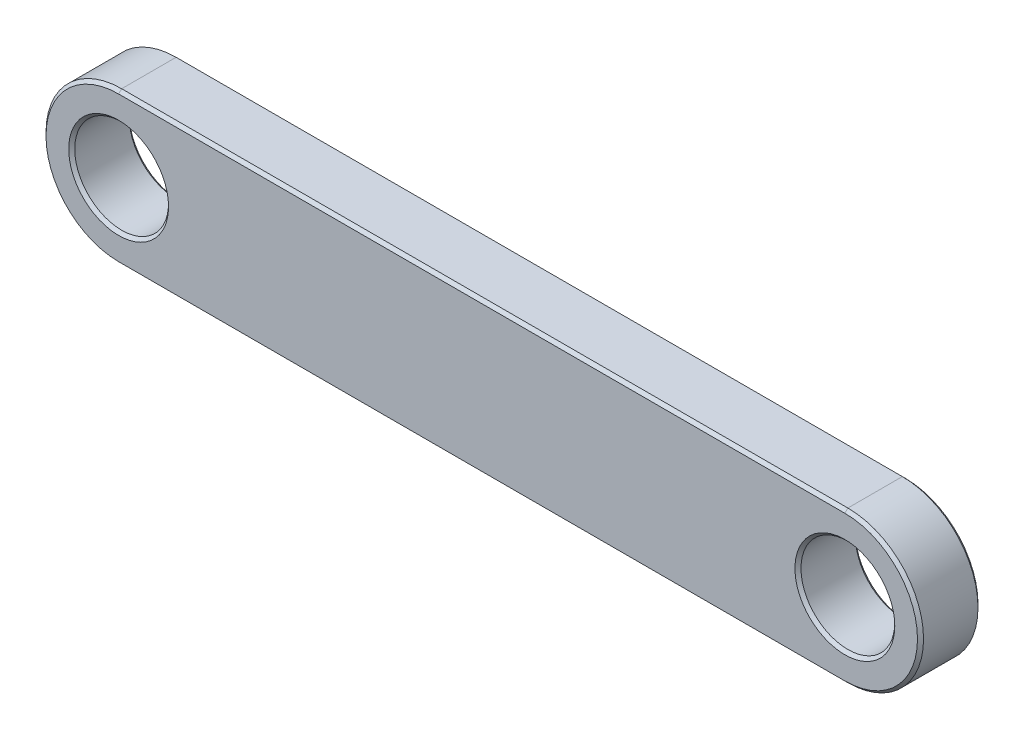
SolidWorks part; units mm, degrees
ref_plane "Front Plane" through (0, 0, 0) normal (0, 0, 1) x (1, 0, 0)
ref_plane "Top Plane" through (0, 0, 0) normal (0, 1, 0) x (1, 0, 0)
ref_plane "Right Plane" through (0, 0, 0) normal (1, 0, 0) x (0, 0, -1)
sketch "Sketch1" plane through (0, 0, 0) normal (0, 0, 1) x (1, 0, 0)
  line L0 (-12, 0) -> (12, 0) construction
  line L1 (-12, 2.5) -> (12, 2.5)
  line L2 (-12, -2.5) -> (12, -2.5)
  arc A0 (-12, 2.5) -> (-12, -2.5) centre (-12, 0) ccw
  arc A1 (12, -2.5) -> (12, 2.5) centre (12, 0) ccw
  circle A2 centre (-12, 0) radius 1.55
  circle A3 centre (12, 0) radius 1.55
  point P2 (0, 0)
  dimension "D2" = 2.5
  dimension "D3" = 3.1
  dimension "D4" = 3.1
  dimension "D1" = 24
extrude "Boss-Extrude1" add sketch "Sketch1" along normal blind 2
chamfer "Chamfer1" distance 0.1 angle 45 12 edges at (13.55, 0, 0) (-10.45, 0, 0) (0, -2.5, 0) (14.5, 0, 0) (0, 2.5, 0) (-14.5, 0, 0) (13.55, 0, 2) (0, 2.5, 2) (14.5, 0, 2) (0, -2.5, 2) (-14.5, 0, 2) (-10.45, 0, 2)
